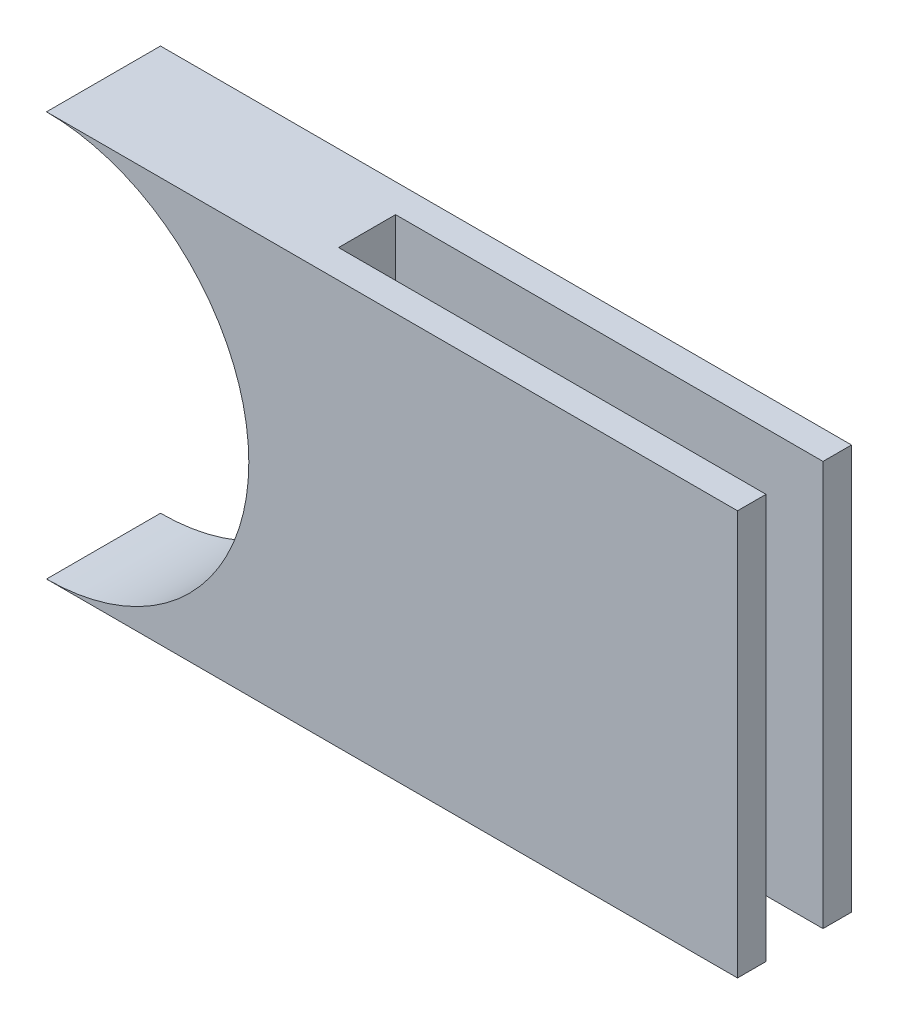
SolidWorks part; units mm, degrees
ref_plane "Front Plane" through (0, 0, 0) normal (0, 0, 1) x (1, 0, 0)
ref_plane "Top Plane" through (0, 0, 0) normal (0, 1, 0) x (1, 0, 0)
ref_plane "Right Plane" through (0, 0, 0) normal (1, 0, 0) x (0, 0, -1)
sketch "Sketch1" plane through (0, 0, 0) normal (0, 0, 1) x (1, 0, 0)
  circle A0 centre (0, 0) radius 19.939
  dimension "D1" = 39.878
extrude "circle extrude" add sketch "Sketch1" along normal blind 7.62
sketch "Sketch3" plane through (0, 0, 0) normal (1, 0, 0) x (0, 0, -1)
  line L0 (0, 55) -> (0, -55) construction
  line L1 (-7.62, 19.939) -> (0, 19.939)
  line L2 (-7.62, 19.939) -> (-7.62, -19.939)
  line L3 (-7.62, -19.939) -> (0, -19.939)
  line L4 (0, 19.939) -> (0, -19.939)
  line L5 (-7.62, -19.939) -> (0, -19.939) construction
extrude "rectangle extrude" add sketch "Sketch3" along normal blind 63.5
sketch "Sketch2" plane through (0, 0, 7.62) normal (0, 0, 1) x (1, 0, 0)
  circle A0 centre (0, 0) radius 18.034
  dimension "D1" = 36.068
extrude "cricle cut" cut sketch "Sketch2" against normal through all
sketch "Sketch4" plane through (0, 0, 7.62) normal (0, 0, 1) x (1, 0, 0)
  line L0 (63.5, 19.939) -> (63.5, -19.939) construction
  line L1 (0, 18.034) -> (61.595, 18.034)
  line L2 (0, 18.034) -> (0, -18.034)
  line L3 (0, -18.034) -> (61.595, -18.034)
  line L4 (61.595, 18.034) -> (61.595, -18.034)
  line L5 (63.5, -19.939) -> (0, -19.939) construction
  circle A0 centre (0, 0) radius 18.034 construction
  dimension "D1" = 1.905
  dimension "D2" = 1.905
extrude "frame cut" cut sketch "Sketch4" against normal through all flip side to cut
sketch "Sketch8" plane through (0, 0, 7.62) normal (0, 0, 1) x (1, 0, 0)
  line L6 (0, -18.034) -> (61.595, -18.034) construction
  line L7 (36.068, 18.034) -> (61.595, 18.034)
  line L8 (61.595, 18.034) -> (61.595, -18.034)
  line L9 (61.595, -18.034) -> (36.068, -18.034)
  line L10 (61.595, 18.034) -> (0, 18.034) construction
  arc A1 (36.068, -18.034) -> (36.068, 18.034) centre (36.068, 0) ccw
  dimension "D1" = 36.068
extrude "end cut" [suppressed] cut sketch "Sketch8" against normal through all
sketch "Sketch10" plane through (0, 0, 0) normal (0, 0, -1) x (-1, 0, 0)
  line L2 (0, 18.034) -> (-61.595, 18.034)
  line L3 (-61.595, -18.034) -> (0, -18.034)
  line L4 (0, 18.034) -> (-61.595, 18.034)
  line L5 (-61.595, -18.034) -> (0, -18.034)
  line L7 (-61.595, 18.034) -> (-61.595, -18.034)
  line L8 (-61.595, 18.034) -> (-61.595, -18.034)
  arc A3 (0, 18.034) -> (0, -18.034) centre (0, 0) ccw
  arc A5 (0, 18.034) -> (0, -18.034) centre (0, 0) ccw
  dimension "D1" = 0
extrude "extension" add sketch "Sketch10" along normal blind 2.54
ref_plane "Plane2" [suppressed] through (20.32, 0, 0) normal (1, 0, 0) x (0, 0, -1)
sketch "Sketch11" [suppressed] plane through (20.32, 0, 0) normal (1, 0, 0) x (0, 0, -1)
  line L0 (2.54, 18.034) -> (-7.62, 18.034) construction
  line L1 (0, -18.034) -> (-5.08, -18.034)
  line L2 (0, -18.034) -> (0, 18.034)
  line L3 (0, 18.034) -> (-5.08, 18.034)
  line L4 (-5.08, -18.034) -> (-5.08, 18.034)
  line L5 (0, -18.034) -> (-5.08, 18.034) construction
  line L6 (0, 18.034) -> (-5.08, -18.034) construction
  line L7 (2.54, -18.034) -> (-7.62, -18.034) construction
  point P0 (-2.54, 0)
  dimension "D1" = 2.54
  dimension "D2" = 5.08
extrude "middle" [suppressed] cut sketch "Sketch11" along normal through all
sketch "Sketch12" [suppressed] plane through (0, 0, 0) normal (0, 0, 1) x (1, 0, 0)
  line L0 (20.32, -5.588) -> (20.32, 5.588) construction
  line L1 (0, 18.034) -> (61.595, 18.034) construction
  line L2 (2.286, 18.034) -> (0, 18.034)
  line L3 (0, 18.034) -> (0, -18.034)
  line L4 (0, -18.034) -> (2.286, -18.034)
  arc A0 (2.286, -18.034) -> (2.286, 18.034) centre (2.286, 0) ccw
  dimension "D1" = 36.068
extrude "circle extension" [suppressed] cut sketch "Sketch12" along normal blind 5.08 flip side to cut
sketch "Sketch13" plane through (61.595, 0, 0) normal (1, 0, 0) x (0, 0, -1)
  line L1 (0, -18.034) -> (-5.08, -18.034)
  line L2 (0, -18.034) -> (0, 18.034)
  line L3 (0, 18.034) -> (-5.08, 18.034)
  line L4 (-5.08, -18.034) -> (-5.08, 18.034)
  line L5 (0, -18.034) -> (-5.08, 18.034) construction
  line L6 (0, 18.034) -> (-5.08, -18.034) construction
  line L7 (2.54, -18.034) -> (-7.62, -18.034) construction
  line L8 (2.54, 18.034) -> (-7.62, 18.034) construction
  point P0 (-2.54, 0)
  point P7 (0, 0)
  point P9 (0, 0)
  point P12 (0, 0)
  dimension "D1" = 2.54
  dimension "D2" = 5.08
extrude "Cut-Extrude1" cut sketch "Sketch13" against normal blind 38.1
sketch "Sketch14" plane through (23.495, 0, 0) normal (1, 0, 0) x (0, 0, -1)
  circle A0 centre (-2.54, 0) radius 1.905
  dimension "D2" = 3.81
  dimension "D1" = 2.54
extrude "Boss-Extrude3" add sketch "Sketch14" along normal blind 2.54
